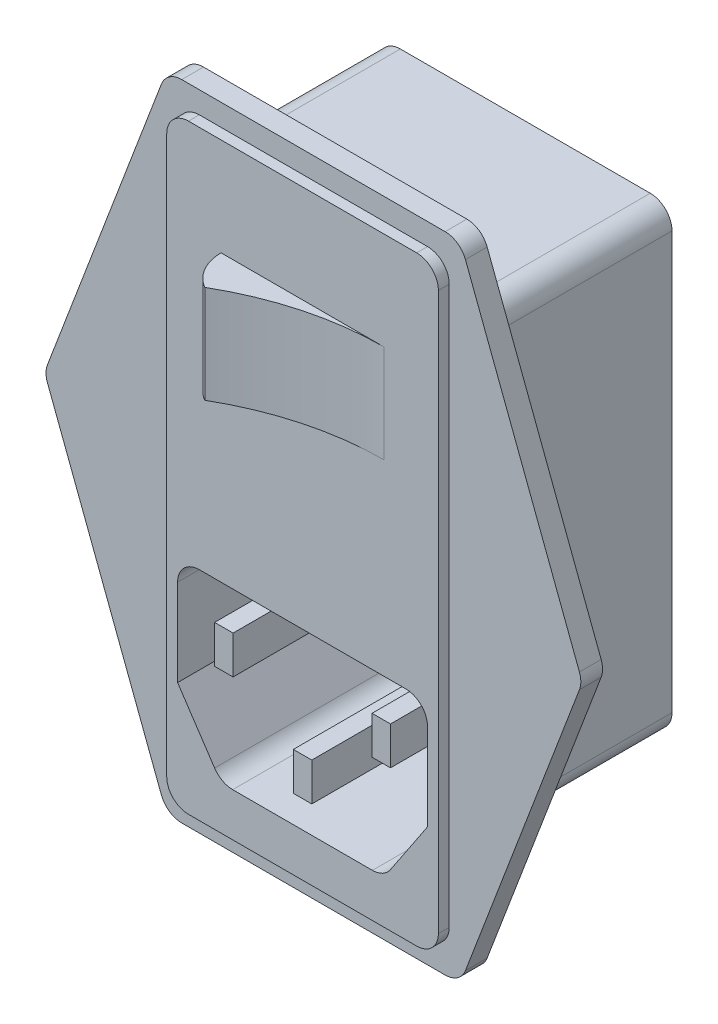
SolidWorks part; units mm, degrees
ref_plane "Спереди" through (0, 0, 0) normal (0, 0, 1) x (1, 0, 0)
ref_plane "Сверху" through (0, 0, 0) normal (0, 1, 0) x (1, 0, 0)
ref_plane "Справа" through (0, 0, 0) normal (1, 0, 0) x (0, 0, -1)
sketch "Эскиз1" plane through (0, 0, 0) normal (0, 0, 1) x (1, 0, 0)
  line L0 (0, 0) -> (27, 0)
  line L1 (0, 0) -> (0, -41.25)
  line L2 (27, 0) -> (27, -41.25)
  line L3 (0, -41.25) -> (27, -41.25) construction
  line L4 (13.5, 0) -> (13.5, -41.25) construction
  line L5 (13.5, -41.25) -> (13.5, -47.25) construction
  line L6 (6.25, -47.25) -> (20.75, -47.25)
  line L7 (0, -41.25) -> (6.25, -47.25)
  line L8 (20.75, -47.25) -> (27, -41.25)
  dimension "D1" = 27
  dimension "D2" = 41.25
  dimension "D3" = 47.25
  dimension "D4" = 14.5
extrude "Бобышка-Вытянуть1" add sketch "Эскиз1" along normal blind 17.5
sketch "Эскиз2" plane through (0, 0, 17.5) normal (0, 0, 1) x (1, 0, 0)
  line L0 (13.5, 0) -> (13.5, -47.25) construction
  line L1 (27, 0) -> (0, 0) construction
  line L2 (6.25, -47.25) -> (20.75, -47.25) construction
  line L3 (13.5, 0) -> (13.5, 7) construction
  line L4 (13.5, -47.25) -> (13.5, -52.25) construction
  line L5 (0, 7) -> (27, 7)
  line L6 (0, -52.25) -> (27, -52.25)
  line L7 (27, 7) -> (27, -52.25) construction
  line L8 (27, -22.625) -> (13.5, -22.625) construction
  line L9 (38.25, -22.625) -> (-11.25, -22.625) construction
  line L10 (0, 7) -> (-11.25, -22.625)
  line L11 (-11.25, -22.625) -> (0, -52.25)
  line L12 (27, 7) -> (38.25, -22.625)
  line L13 (38.25, -22.625) -> (27, -52.25)
  dimension "D1" = 5
  dimension "D2" = 7
  dimension "D3" = 27
  dimension "D4" = 49.5
extrude "Бобышка-Вытянуть2" add sketch "Эскиз2" along normal blind 2
sketch "Эскиз3" plane through (0, 0, 19.5) normal (0, 0, 1) x (1, 0, 0)
  line L0 (13.5, 7) -> (13.5, -52.25) construction
  line L1 (27, 7) -> (0, 7) construction
  line L2 (0, -52.25) -> (27, -52.25) construction
  line L3 (1, 5) -> (26, 5)
  line L4 (1, 5) -> (1, -50.25)
  line L5 (26, 5) -> (26, -50.25)
  line L6 (1, -50.25) -> (26, -50.25)
  line L7 (26, -22.625) -> (1, -22.625) construction
  point P10 (13.5, -22.625)
  dimension "D1" = 2
  dimension "D2" = 25
extrude "Бобышка-Вытянуть3" add sketch "Эскиз3" along normal blind 1
fillet "Скругление1" radius 2 4 edges at (0, 7, 18.5) (27, -52.25, 18.5) (38.25, -22.625, 18.5) (27, 7, 18.5)
fillet "Скругление2" radius 2 2 edges at (0, -52.25, 18.5) (-11.25, -22.625, 18.5)
fillet "Скругление3" radius 2 4 edges at (26, 5, 20) (26, -50.25, 20) (1, -50.25, 20) (1, 5, 20)
sketch "Эскиз4" plane through (0, 0, 20.5) normal (0, 0, 1) x (1, 0, 0)
  line L0 (13.5, 5) -> (13.5, -50.25) construction
  line L1 (24, 5) -> (3, 5) construction
  line L2 (3, -50.25) -> (24, -50.25) construction
  line L3 (6, -4) -> (21, -4)
  line L4 (6, -4) -> (6, -13)
  line L5 (21, -4) -> (21, -13)
  line L6 (6, -13) -> (21, -13)
  line L7 (13.5, -4) -> (13.5, -13) construction
  dimension "D1" = 9
  dimension "D2" = 15
  dimension "D3" = 9
extrude "Бобышка-Вытянуть4" add sketch "Эскиз4" along normal blind 3.5
sketch "Эскиз5" plane through (0, -4, 0) normal (0, 1, 0) x (1, 0, 0)
  line L0 (21, -24) -> (6, -24) construction
  line L1 (6, -24) -> (6, -20.5) construction
  line L2 (6, -24) -> (6, -20.5)
  line L3 (21, -24) -> (6, -24)
  line L4 (21, -20.5) -> (6, -20.5) construction
  line L5 (21, -24) -> (21, -20.5) construction
  line L6 (21, -24) -> (21, -20.5)
  arc A0 (21, -20.5) -> (8, -24) centre (21, -46.3929) ccw
  arc A1 (6, -20.5) -> (8, -24) centre (10.0625, -20.5) ccw
  point P2 (8, -24)
  line M3 (6, -20.5) -> (6, -24)
  line M4 (6, -24) -> (21, -24)
  line M5 (21, -24) -> (21, -20.5)
  dimension "D1" = 2
extrude "Вырез-Вытянуть1" cut sketch "Эскиз5" against normal up to surface (9 mm away) contours A0 L3 M5 | A1 M3 M4 up to face at (13.5, -13, 22.25)
sketch "Эскиз6" plane through (0, 0, 20.5) normal (0, 0, 1) x (1, 0, 0)
  line L0 (4, -30.25) -> (23, -30.25)
  line L1 (2, -30.25) -> (2, -46.25) construction
  line L2 (25, -30.25) -> (25, -46.25) construction
  line L3 (2, -46.25) -> (25, -46.25) construction
  line L4 (3, -50.25) -> (24, -50.25) construction
  line L5 (13.5, 5) -> (13.5, -50.25) construction
  line L6 (24, 5) -> (3, 5) construction
  line L7 (2, -40.25) -> (5.4063, -45.3594)
  line L8 (7.0704, -46.25) -> (19.9296, -46.25)
  line L9 (2, -32.25) -> (2, -40.25)
  line L10 (2, -40.25) -> (25, -40.25) construction
  line L11 (21.5937, -45.3594) -> (25, -40.25)
  line L12 (25, -40.25) -> (25, -32.25)
  line L13 (5.4063, -33.75) -> (5.4063, -37.25)
  line L14 (5.4063, -33.75) -> (7.1063, -33.75)
  line L15 (5.4063, -37.25) -> (7.1063, -37.25)
  line L16 (7.1063, -33.75) -> (7.1063, -37.25)
  line L17 (19.8937, -33.75) -> (21.5937, -33.75)
  line L18 (19.8937, -33.75) -> (19.8937, -37.25)
  line L19 (21.5937, -33.75) -> (21.5937, -37.25)
  line L20 (19.8937, -37.25) -> (21.5937, -37.25)
  line L21 (12.65, -40.25) -> (14.35, -40.25)
  line L22 (12.65, -40.25) -> (12.65, -43.75)
  line L23 (14.35, -40.25) -> (14.35, -43.75)
  line L24 (12.65, -43.75) -> (14.35, -43.75)
  line L25 (7.1063, -37.25) -> (19.8937, -37.25) construction
  arc A0 (7.0704, -46.25) -> (5.4063, -45.3594) centre (7.0704, -44.25) cw
  arc A1 (19.9296, -46.25) -> (21.5937, -45.3594) centre (19.9296, -44.25) ccw
  arc A2 (25, -32.25) -> (23, -30.25) centre (23, -32.25) ccw
  arc A3 (4, -30.25) -> (2, -32.25) centre (4, -32.25) ccw
  point P8 (13.5, -30.25)
  point P13 (13.5, -46.25)
  point P18 (6, -46.25)
  point P21 (21, -46.25)
  point P28 (13.5, -37.25)
  point P35 (13.5, -40.25)
  dimension "D6" = 2
  dimension "D1" = 4
  dimension "D2" = 23
  dimension "D3" = 16
  dimension "D4" = 15
  dimension "D5" = 10
  dimension "D7" = 1.7
  dimension "D8" = 3.5
  dimension "D9" = 3
extrude "Вырез-Вытянуть2" cut sketch "Эскиз6" against normal blind 18
fillet "Скругление4" radius 2 6 edges at (6.25, -47.25, 8.75) (0, -41.25, 8.75) (0, 0, 8.75) (20.75, -47.25, 8.75) (27, -41.25, 8.75) (27, 0, 8.75)
sketch "Эскиз7" plane through (0, 0, 0) normal (0, 0, -1) x (-1, 0, 0)
  line L0 (-23.5, -1.5) -> (-3.5, -1.5)
  line L1 (-25.5, -3.5) -> (-25.5, -14.5)
  line L2 (-1.5, -3.5) -> (-1.5, -14.5)
  line L3 (-23.5, -16.5) -> (-3.5, -16.5)
  line L4 (-27, -40.3976) -> (-27, -2) construction
  line L5 (-25, 0) -> (-2, 0) construction
  line L6 (0, -2) -> (0, -40.3976) construction
  arc A0 (-23.5, -16.5) -> (-25.5, -14.5) centre (-23.5, -14.5) cw
  arc A1 (-3.5, -16.5) -> (-1.5, -14.5) centre (-3.5, -14.5) ccw
  arc A2 (-1.5, -3.5) -> (-3.5, -1.5) centre (-3.5, -3.5) ccw
  arc A3 (-25.5, -3.5) -> (-23.5, -1.5) centre (-23.5, -3.5) cw
  point P14 (-1.5, -16.5)
  point P17 (-1.5, -1.5)
  dimension "D5" = 2
  dimension "D1" = 1.5
  dimension "D2" = 1.5
  dimension "D3" = 1.5
  dimension "D4" = 15
extrude "Вырез-Вытянуть3" cut sketch "Эскиз7" against normal blind 7
sketch "Эскиз8" plane through (0, 0, 0) normal (0, 0, -1) x (-1, 0, 0)
  line L0 (-7, -19.5) -> (-2, -19.5)
  line L1 (-7, -19.5) -> (-7, -20.5)
  line L2 (-2, -19.5) -> (-2, -20.5)
  line L3 (-7, -20.5) -> (-2, -20.5)
  line L4 (-7, -32.5) -> (-2, -32.5)
  line L5 (-7, -32.5) -> (-7, -33.5)
  line L6 (-2, -32.5) -> (-2, -33.5)
  line L7 (-7, -33.5) -> (-2, -33.5)
  line L8 (-16, -43.25) -> (-11, -43.25)
  line L9 (-16, -43.25) -> (-16, -44.25)
  line L10 (-11, -43.25) -> (-11, -44.25)
  line L11 (-16, -44.25) -> (-11, -44.25)
  line L12 (0, -2) -> (0, -40.3976) construction
  line L13 (-13.5, -16.5) -> (-13.5, -47.25) construction
  line L14 (-23.5, -16.5) -> (-3.5, -16.5) construction
  line L15 (-7.0546, -47.25) -> (-19.9454, -47.25) construction
  point P20 (-13.5, -43.25)
  dimension "D1" = 1
  dimension "D2" = 5
  dimension "D3" = 2
  dimension "D4" = 12
  dimension "D5" = 3
  dimension "D6" = 3
extrude "Бобышка-Вытянуть5" add sketch "Эскиз8" along normal blind 9.5
sketch "Эскиз9" plane through (0, 0, 7) normal (0, 0, -1) x (-1, 0, 0)
  line L0 (-7.5, -6.5) -> (-6.5, -6.5)
  line L1 (-7.5, -6.5) -> (-7.5, -11.5)
  line L2 (-6.5, -6.5) -> (-6.5, -11.5)
  line L3 (-7.5, -11.5) -> (-6.5, -11.5)
  line L4 (-14.5, -6.5) -> (-13.5, -6.5)
  line L5 (-14.5, -6.5) -> (-14.5, -11.5)
  line L6 (-13.5, -6.5) -> (-13.5, -11.5)
  line L7 (-14.5, -11.5) -> (-13.5, -11.5)
  line L8 (-1.5, -14.5) -> (-1.5, -3.5) construction
  line L9 (-1.5, -9) -> (-25.5, -9) construction
  line L10 (-1.5, -14.5) -> (-1.5, -3.5) construction
  line L14 (-25.5, -3.5) -> (-25.5, -14.5) construction
  point P17 (-6.5, -9)
  dimension "D1" = 1
  dimension "D2" = 5
  dimension "D3" = 7
  dimension "D4" = 5
extrude "Бобышка-Вытянуть6" add sketch "Эскиз9" along normal up to surface (7 mm away) up to face at (4.5, -33, 0)
